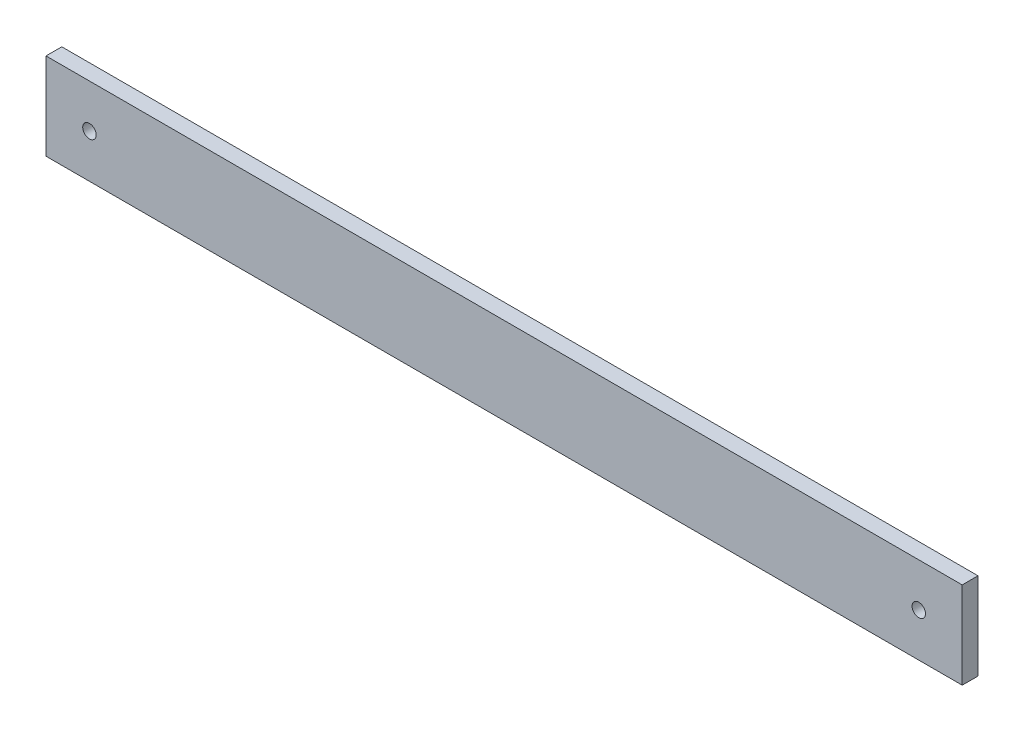
SolidWorks part; units mm, degrees
ref_plane "前视基准面" through (0, 0, 0) normal (0, 0, 1) x (1, 0, 0)
ref_plane "上视基准面" through (0, 0, 0) normal (0, 1, 0) x (1, 0, 0)
ref_plane "右视基准面" through (0, 0, 0) normal (1, 0, 0) x (0, 0, -1)
other "Configuration Table"
sketch "草图1" plane through (0, 0, 0) normal (0, 0, 1) x (1, 0, 0)
  line L1 (-11, -11) -> (221, -11)
  line L2 (-11, -11) -> (-11, 11)
  line L3 (-11, 11) -> (221, 11)
  line L4 (221, -11) -> (221, 11)
  line L5 (-11, -11) -> (221, 11) construction
  line L6 (-11, 11) -> (221, -11) construction
  circle A0 centre (0, 0) radius 1.7
  circle A1 centre (210, 0) radius 1.7
  point P0 (105, 0)
extrude "凸台-拉伸1" add sketch "草图1" along normal mid plane 4
